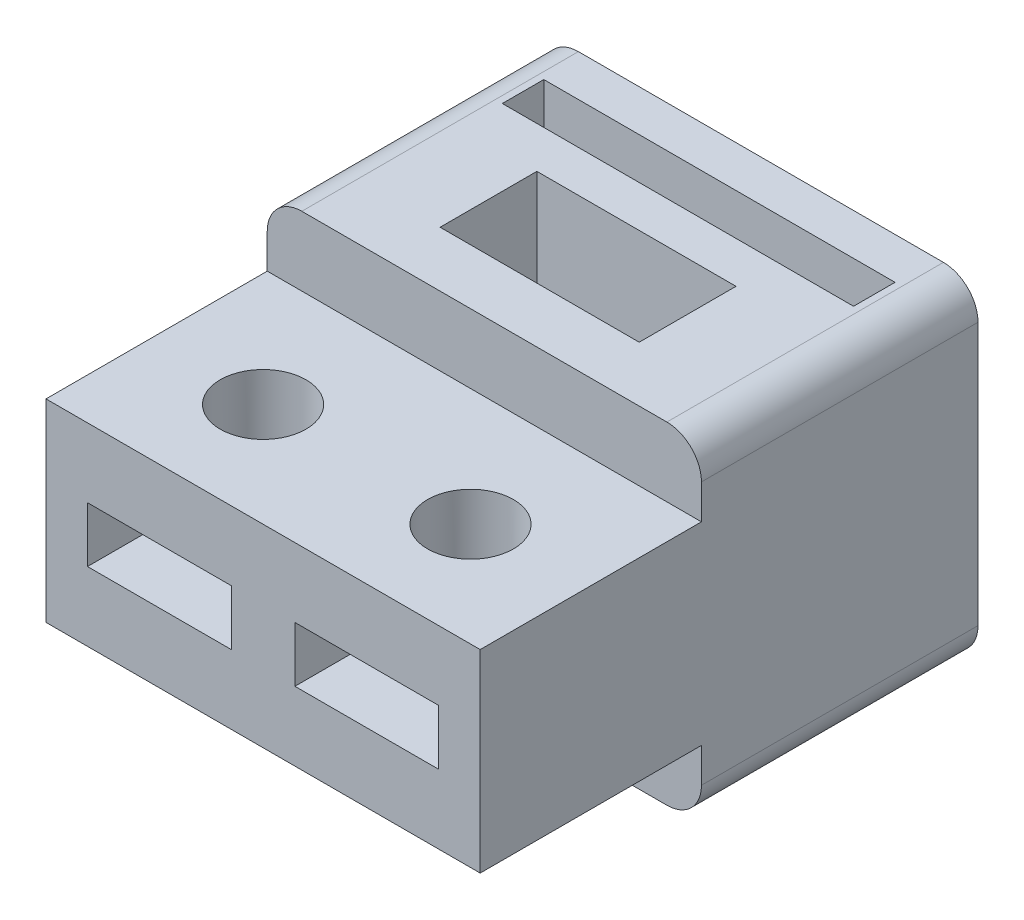
SolidWorks part; units mm, degrees
ref_plane "Front Plane" through (0, 0, 0) normal (0, 0, 1) x (1, 0, 0)
ref_plane "Top Plane" through (0, 0, 0) normal (0, 1, 0) x (1, 0, 0)
ref_plane "Right Plane" through (0, 0, 0) normal (1, 0, 0) x (0, 0, -1)
sketch "Sketch1" plane through (0, 0, 0) normal (0, 1, 0) x (1, 0, 0)
  line L8 (-7.85, 2.25) -> (-7.85, -15.75)
  line L13 (-6.35, 0.75) -> (6.35, 0.75)
  line L14 (-6.35, 0.75) -> (-6.35, -0.75)
  line L19 (-6.35, -0.75) -> (6.35, -0.75)
  line L20 (6.35, 0.75) -> (6.35, -0.75)
  line L21 (0, -0.75) -> (0, 0.75) construction
  line L22 (-6.35, 0) -> (6.35, 0) construction
  line L23 (-7.85, 2.25) -> (7.85, 2.25)
  line L25 (-7.85, -15.75) -> (7.85, -15.75)
  line L31 (7.85, 2.25) -> (7.85, -15.75)
  point P0 (0, 0)
  point P18 (0, -15.75)
  point P19 (0, 2.25)
  dimension "D1" = 1.5
  dimension "D2" = 1.5
  dimension "D3" = 18
  dimension "D4" = 12.7
  dimension "D5" = 1.5
extrude "Boss-Extrude1" add sketch "Sketch1" along normal blind 12
sketch "Sketch2" plane through (0, 0, 15.75) normal (0, 0, 1) x (1, 0, 0)
  line L0 (-3.6, 12) -> (-3.6, 8.0785)
  line L1 (-7.85, 12) -> (7.85, 12) construction
  line L2 (3.6, 8.0785) -> (3.6, 12)
  line L3 (3.6, 3.9215) -> (3.6, 8.0785)
  line L4 (3.6, 8.0785) -> (0, 10.1569)
  line L5 (0, 10.1569) -> (-3.6, 8.0785)
  line L6 (-3.6, 8.0785) -> (-3.6, 3.9215)
  line L7 (-3.6, 3.9215) -> (0, 1.8431)
  line L8 (0, 1.8431) -> (3.6, 3.9215)
  circle A0 centre (0, 6) radius 3.6 construction
  line M10 (7.85, 12) -> (-7.85, 12)
  dimension "D1" = 7.2
  dimension "D2" = 6
extrude "Cut-Extrude1" cut sketch "Sketch2" against normal blind 3.5 from offset 10 contours L5 L4 L2 L0 M10 | L7 L8 L3 L4 L5 L6 offset against normal yes
hole_wizard "M4 Clearance Hole2" positions "Sketch7" profile "Sketch8" hole size "M4" standard "ISO"
sketch "Sketch7" plane through (0, 0, -2.25) normal (0, 0, -1) x (-1, 0, 0)
  line L1 (0, 12) -> (0, 0) construction
  line L2 (-7.85, 12) -> (7.85, 12) construction
  line L3 (-7.85, 0) -> (7.85, 0) construction
  point P0 (0, 6)
sketch "Sketch8" plane through (0, 6, -2.25) normal (1, 0, 0) x (0, 1, 0)
  line L0 (0, 0) -> (0, 11.4421)
  line L1 (0, 11.4421) -> (2.4, 10)
  line L2 (2.4, 10) -> (2.4, 0)
  line L5 (2.4, 0) -> (0, 0)
  line L10 (0, 11.4421) -> (-2.4, 10) construction
  line L11 (0, -6.35) -> (0, 107.95) construction
  dimension "Hole Dia." = 4.8
  dimension "Hole Depth" = 10
  dimension "Drill Angle" = 118
hole_wizard "M2.5 Clearance Hole1" positions "Sketch12" profile "Sketch11" hole size "M2.5" standard "ISO"
sketch "Sketch12" plane through (0, 12, 0) normal (0, 1, 0) x (1, 0, 0)
  line L0 (-3.75, -12) -> (3.75, -12) construction
  line L3 (-2.2345, -14.625) -> (-0.7189, -12) construction
  line L4 (-0.7189, -12) -> (-2.2345, -9.375) construction
  line L5 (-2.2345, -9.375) -> (-5.2655, -9.375) construction
  line L6 (-5.2655, -9.375) -> (-6.7811, -12) construction
  line L7 (-6.7811, -12) -> (-5.2655, -14.625) construction
  line L8 (-5.2655, -14.625) -> (-2.2345, -14.625) construction
  line L10 (5.2655, -14.625) -> (6.7811, -12) construction
  line L11 (6.7811, -12) -> (5.2655, -9.375) construction
  line L12 (5.2655, -9.375) -> (2.2345, -9.375) construction
  line L13 (2.2345, -9.375) -> (0.7189, -12) construction
  line L14 (0.7189, -12) -> (2.2345, -14.625) construction
  line L15 (2.2345, -14.625) -> (5.2655, -14.625) construction
  circle A0 centre (-3.75, -12) radius 2.625 construction
  circle A1 centre (3.75, -12) radius 2.625 construction
  point P0 (3.75, -12)
  point P2 (-3.75, -12)
  point P13 (0, -12)
  dimension "D1" = 12
  dimension "D2" = 5.25
  dimension "D3" = 7.5
sketch "Sketch11" plane through (3.75, 12, 12) normal (1, 0, 0) x (0, 0, 1)
  line L0 (0, 0) -> (0, 10.9313)
  line L1 (0, 10.9313) -> (1.55, 10)
  line L2 (1.55, 10) -> (1.55, 0)
  line L5 (1.55, 0) -> (0, 0)
  line L10 (0, 10.9313) -> (-1.55, 10) construction
  line L11 (0, -6.35) -> (0, 107.95) construction
  dimension "Hole Dia." = 3.1
  dimension "Hole Depth" = 10
  dimension "Drill Angle" = 118
sketch "Sketch9" plane through (0, 12, 0) normal (0, 1, 0) x (1, 0, 0)
  line L0 (-6.35, -13.5011) -> (-6.35, -15.75)
  line L2 (-1.15, -13.5011) -> (-1.15, -10.4989)
  line L9 (-1.15, -10.4989) -> (-3.75, -8.9978)
  line L10 (-3.75, -8.9978) -> (-6.35, -10.4989)
  line L12 (-6.35, -10.4989) -> (-6.35, -13.5011)
  line L13 (-6.35, -13.5011) -> (-3.75, -15.0022)
  line L14 (-3.75, -15.0022) -> (-1.15, -13.5011)
  line L15 (6.35, -13.5011) -> (6.35, -10.4989)
  line L16 (6.35, -10.4989) -> (3.75, -8.9978)
  line L17 (3.75, -8.9978) -> (1.15, -10.4989)
  line L18 (1.15, -10.4989) -> (1.15, -13.5011)
  line L19 (1.15, -13.5011) -> (3.75, -15.0022)
  line L20 (3.75, -15.0022) -> (6.35, -13.5011)
  line L21 (-7.85, -15.75) -> (7.85, -15.75) construction
  line L22 (-1.15, -13.5011) -> (-1.15, -15.75)
  line L23 (-1.15, -15.75) -> (-6.35, -15.75)
  line L24 (1.15, -13.5011) -> (1.15, -15.75)
  line L25 (1.15, -15.75) -> (6.35, -15.75)
  line L26 (6.35, -15.75) -> (6.35, -13.5011)
  circle A0 centre (-3.75, -12) radius 2.6 construction
  circle A2 centre (3.75, -12) radius 2.6 construction
  line M11 (-7.85, -15.75) -> (7.85, -15.75)
  circle M20 centre (3.75, -12) radius 1.55
  circle M21 centre (-3.75, -12) radius 1.55
  dimension "D1" = 5.2
extrude "Cut-Extrude3" cut sketch "Sketch9" against normal mid plane 2 from offset 6 contours L22 L14 L13 L0 M11 | L13 L14 L2 L9 L10 L12 M21 | L26 L20 L19 L24 M11 | L19 L20 L15 L16 L17 L18 M20 offset against normal yes
sketch "Sketch14" plane through (0, 0, 15.75) normal (0, 0, 1) x (1, 0, 0)
  line L0 (-7.85, 12) -> (7.85, 12) construction
  line L1 (-7.85, 12) -> (7.85, 12)
  line L2 (-7.85, 12) -> (-7.85, 0)
  line L3 (-7.85, 0) -> (7.85, 0)
  line L4 (7.85, 12) -> (7.85, 0)
  line L5 (0, 0) -> (0, 12) construction
  line L6 (-7.85, 6) -> (7.85, 6) construction
  line L7 (-7.85, 9.5) -> (7.85, 9.5)
  line L8 (-7.85, 9.5) -> (-7.85, 2.5)
  line L9 (-7.85, 2.5) -> (7.85, 2.5)
  line L10 (7.85, 9.5) -> (7.85, 2.5)
  line L11 (0, 2.5) -> (0, 9.5) construction
  line L12 (-7.85, 6) -> (7.85, 6) construction
  line L13 (-7.85, 12) -> (-7.85, 0) construction
  point P0 (0, 6)
  point P4 (0, 6)
  line M9 (-7.85, 0) -> (7.85, 0)
  line M10 (7.85, 0) -> (7.85, 12)
  line M11 (7.85, 12) -> (-7.85, 12)
  line M12 (-7.85, 12) -> (-7.85, 0)
  dimension "D1" = 7
extrude "Cut-Extrude5" cut sketch "Sketch14" against normal blind 8 contours L9 M12 M9 M10 | L7 L4 M12 M11
fillet "Fillet1" radius 1.25 4 edges at (-7.85, 0, 2.75) (-7.85, 12, 2.75) (7.85, 12, 2.75) (7.85, 0, 2.75)
